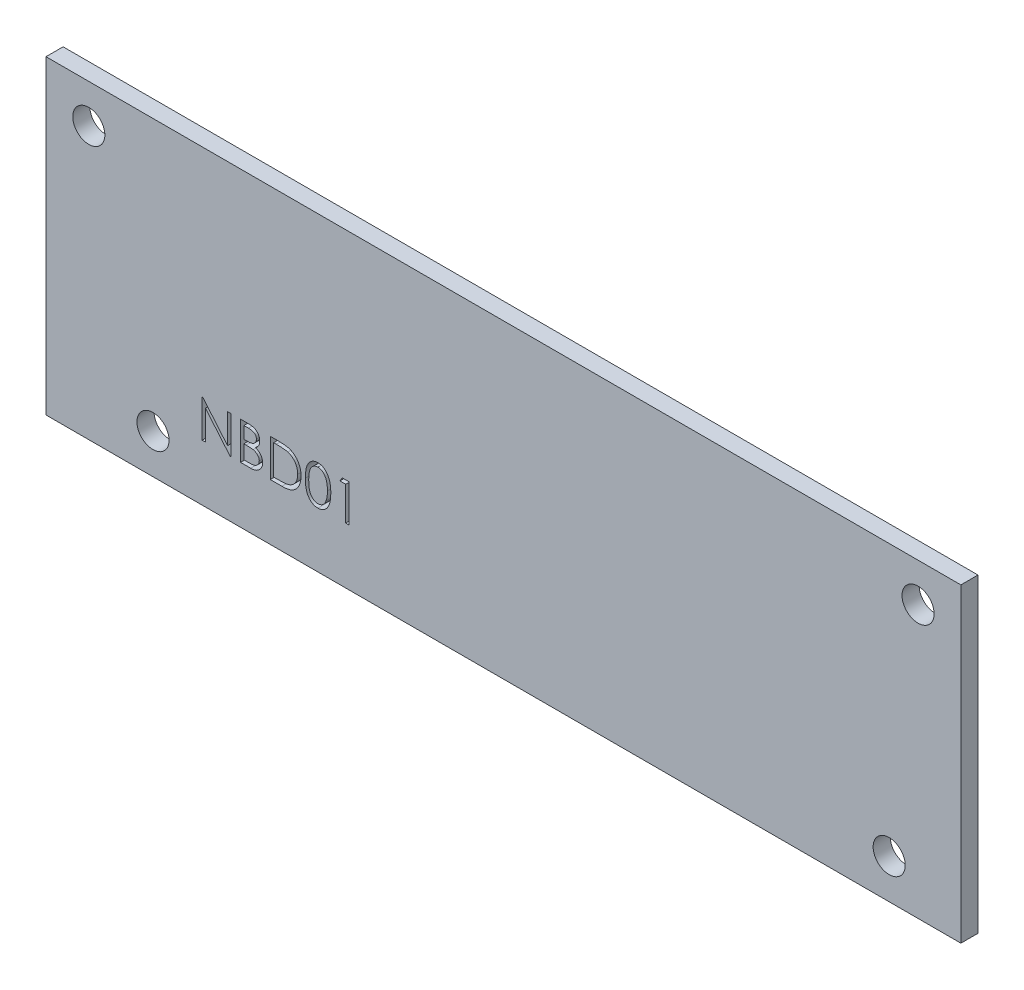
SolidWorks part; units mm, degrees
ref_plane "Piano frontale" through (0, 0, 0) normal (0, 0, 1) x (1, 0, 0)
ref_plane "Piano superiore" through (0, 0, 0) normal (0, 1, 0) x (1, 0, 0)
ref_plane "Piano destro" through (0, 0, 0) normal (1, 0, 0) x (0, 0, -1)
sketch "Schizzo1" plane through (0, 0, 0) normal (0, 0, 1) x (1, 0, 0)
  line L1 (42.75, -14.5) -> (-42.75, -14.5)
  line L2 (42.75, -14.5) -> (42.75, 14.5)
  line L3 (42.75, 14.5) -> (-42.75, 14.5)
  line L4 (-42.75, -14.5) -> (-42.75, 14.5)
  line L5 (42.75, -14.5) -> (-42.75, 14.5) construction
  line L6 (42.75, 14.5) -> (-42.75, -14.5) construction
  point P0 (0, 0)
  dimension "D1" = 85.5
  dimension "D2" = 29
extrude "Estrusione-Estrusione1" add sketch "Schizzo1" along normal blind 1.6
sketch "Schizzo2" plane through (0, 0, 1.6) normal (0, 0, 1) x (1, 0, 0)
  line L0 (-42.75, 14.5) -> (-42.75, -14.5) construction
  line L1 (-42.75, -14.5) -> (42.75, -14.5) construction
  line L2 (42.75, -14.5) -> (42.75, 14.5) construction
  line L3 (42.75, 14.5) -> (-42.75, 14.5) construction
  circle A0 centre (-32.75, -10.8) radius 1.5
  circle A1 centre (36.05, -10.8) radius 1.5
  circle A2 centre (38.75, 10.9) radius 1.5
  circle A3 centre (-38.75, 10.9) radius 1.5
  text T0 "NBD01"
  dimension "D2" = 3
  dimension "D4" = 3
  dimension "D6" = 3
  dimension "D9" = 3
  dimension "D1" = 10
  dimension "D3" = 3.7
  dimension "D5" = 6.7
  dimension "D7" = 3.6
  dimension "D8" = 4
  dimension "D10" = 4
extrude "Taglio-Estrusione1" cut sketch "Schizzo2" against normal blind 1.6
